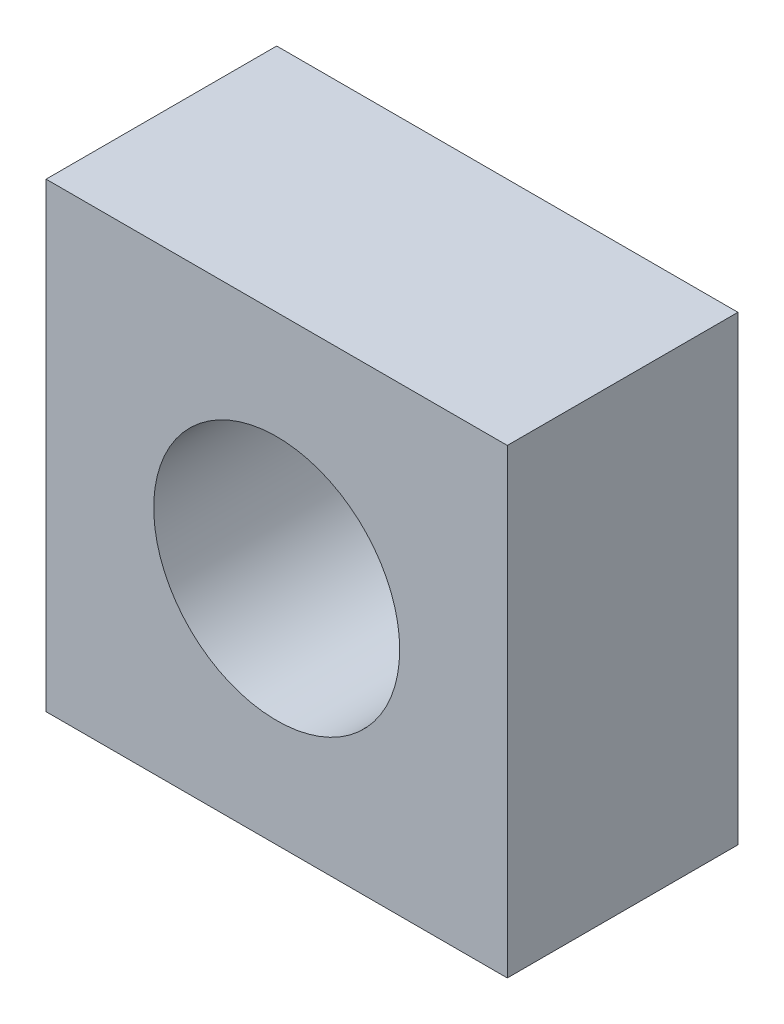
SolidWorks part; units mm, degrees
material "6061-T6 (SS)"
ref_plane "Front Plane" through (0, 0, 0) normal (0, 0, 1) x (1, 0, 0)
ref_plane "Top Plane" through (0, 0, 0) normal (0, 1, 0) x (1, 0, 0)
ref_plane "Right Plane" through (0, 0, 0) normal (1, 0, 0) x (0, 0, -1)
sketch "Sketch1" plane through (0, 0, 0) normal (0, 0, 1) x (1, 0, 0)
  line L1 (0, 0) -> (6, 0)
  line L2 (0, 0) -> (0, 6)
  line L3 (0, 6) -> (6, 6)
  line L4 (6, 0) -> (6, 6)
  circle A0 centre (3, 3) radius 1.6
  point P7 (0, 3)
  point P8 (3, 6)
  dimension "D3" = 3.2
  dimension "D1" = 6
  dimension "D2" = 6
extrude "Boss-Extrude1" add sketch "Sketch1" along normal blind 3
